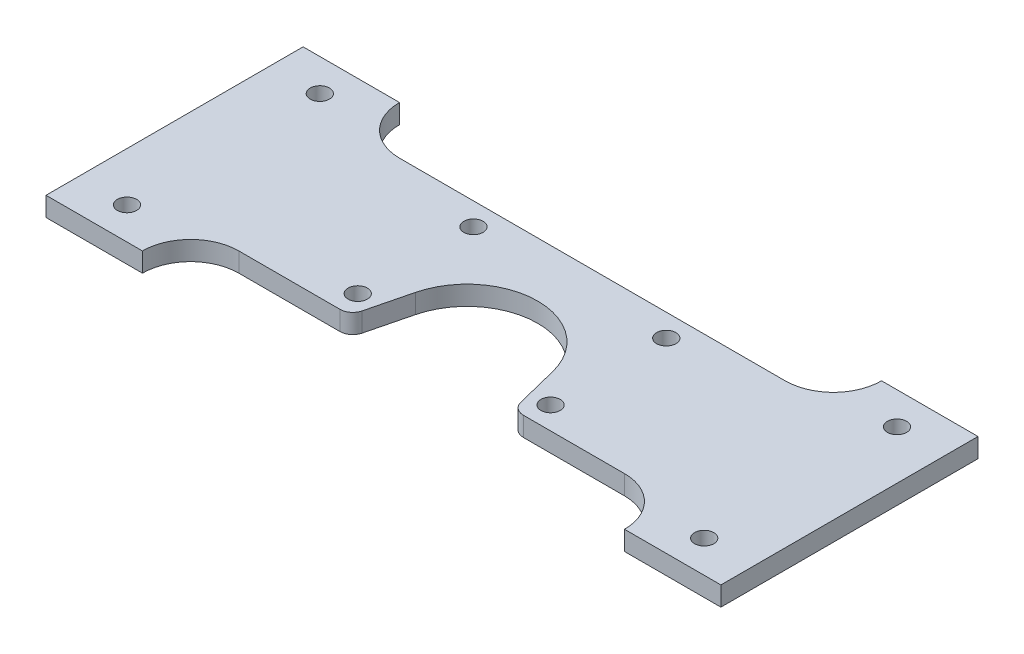
SolidWorks part; units mm, degrees
material "Thornel Mat VMA"
ref_plane "前视基准面" through (0, 0, 0) normal (0, 0, 1) x (1, 0, 0)
ref_plane "上视基准面" through (0, 0, 0) normal (0, 1, 0) x (1, 0, 0)
ref_plane "右视基准面" through (0, 0, 0) normal (1, 0, 0) x (0, 0, -1)
sketch "草图1" plane through (0, 0, 0) normal (0, 1, 0) x (1, 0, 0)
  line L0 (-52.5, 0) -> (52.5, 0) construction
  line L1 (-52.5, 20) -> (-52.5, -20)
  line L2 (-52.5, -20) -> (-37.5, -20)
  line L3 (-30, -12.5) -> (-12.7081, -12.5)
  line L4 (37.5, -20) -> (52.5, -20)
  line L5 (52.5, -20) -> (52.5, 20)
  line L6 (37.5, 20) -> (52.5, 20)
  line L7 (-30, 12.5) -> (30, 12.5)
  line L8 (-52.5, 20) -> (-37.5, 20)
  line L9 (-12.7081, -12.5) -> (-10.6733, -4.3389)
  line L10 (-44.9013, -44.9013) -> (44.9013, -44.9013) construction
  line L11 (-44.9013, -44.9013) -> (-44.9013, 44.9013) construction
  line L12 (-44.9013, 44.9013) -> (44.9013, 44.9013) construction
  line L13 (44.9013, -44.9013) -> (44.9013, 44.9013) construction
  line L14 (-44.9013, -44.9013) -> (44.9013, 44.9013) construction
  line L15 (-44.9013, 44.9013) -> (44.9013, -44.9013) construction
  line L16 (10.6733, -4.3389) -> (12.7081, -12.5)
  line L17 (0, 0) -> (0, -7) construction
  line L18 (12.7081, -12.5) -> (30, -12.5)
  line L20 (-15, -9) -> (15, -9) construction
  line L21 (-15, -9) -> (-15, 9) construction
  line L22 (-15, 9) -> (15, 9) construction
  line L23 (15, -9) -> (15, 9) construction
  line L24 (-15, -9) -> (15, 9) construction
  line L25 (-15, 9) -> (15, -9) construction
  arc A0 (-37.5, -20) -> (-30, -12.5) centre (-30, -20) cw
  arc A1 (30, -12.5) -> (37.5, -20) centre (30, -20) cw
  arc A2 (30, 12.5) -> (37.5, 20) centre (30, 20) ccw
  arc A3 (-37.5, 20) -> (-30, 12.5) centre (-30, 20) ccw
  circle A4 centre (-44.9013, 15) radius 1.5
  circle A5 centre (-44.9013, -15) radius 1.5
  circle A6 centre (44.9013, -15) radius 1.5
  circle A7 centre (44.9013, 15) radius 1.5
  arc A8 (-10.6733, -4.3389) -> (10.6733, -4.3389) centre (0, -7) cw
  circle A9 centre (15, 9) radius 1.5
  circle A10 centre (15, -9) radius 1.5
  circle A11 centre (-15, 9) radius 1.5
  circle A12 centre (-15, -9) radius 1.5
  point P13 (0, 0)
  dimension "D6" = 3
  dimension "D7" = 30
  dimension "D8" = 11
  dimension "D11" = 3
  dimension "D1" = 105
  dimension "D2" = 40
  dimension "D3" = 15
  dimension "D4" = 25
  dimension "D5" = 127
  dimension "D9" = 28
  dimension "D10" = 7
  dimension "D12" = 18
  dimension "D13" = 30
extrude "凸台-拉伸1" add sketch "草图1" along normal blind 3
fillet "圆角1" radius 2 2 edges at (12.7081, 1.5, 12.5) (-12.7081, 1.5, 12.5)
